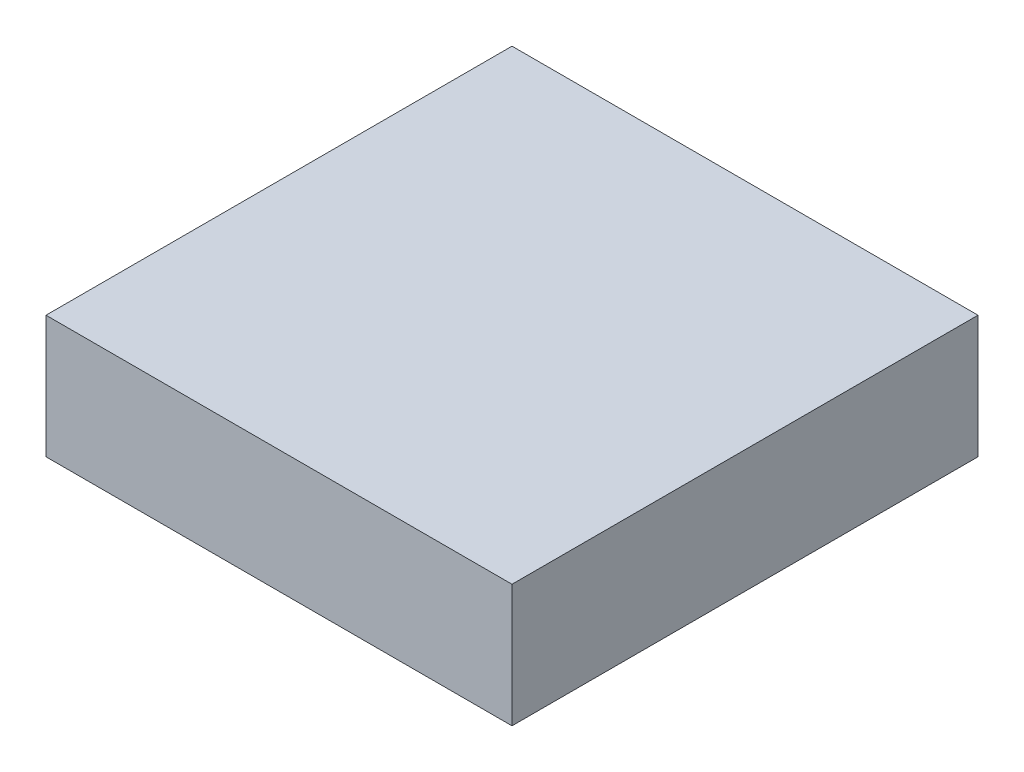
SolidWorks part; units mm, degrees
ref_plane "Front Plane" through (0, 0, 0) normal (0, 0, 1) x (1, 0, 0)
ref_plane "Top Plane" through (0, 0, 0) normal (0, 1, 0) x (1, 0, 0)
ref_plane "Right Plane" through (0, 0, 0) normal (1, 0, 0) x (0, 0, -1)
sketch "Sketch1" plane through (0, 0, 0) normal (0, 1, 0) x (1, 0, 0)
  line L1 (-28.5, 28.5) -> (28.5, 28.5)
  line L2 (-28.5, 28.5) -> (-28.5, -28.5)
  line L3 (-28.5, -28.5) -> (28.5, -28.5)
  line L4 (28.5, 28.5) -> (28.5, -28.5)
  line L5 (0, -28.5) -> (0, 28.5) construction
  line L6 (-28.5, 0) -> (28.5, 0) construction
  point P0 (0, 0)
  dimension "D1" = 57
  dimension "D2" = 57
extrude "Boss-Extrude1" add sketch "Sketch1" along normal blind 15
